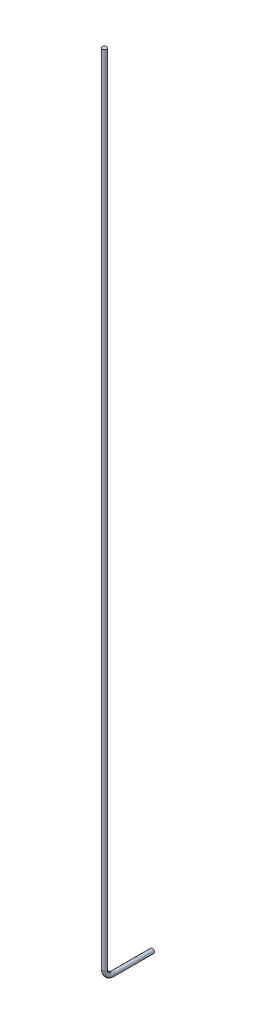
SolidWorks part; units mm, degrees
ref_plane "正面" through (0, 0, 0) normal (0, 0, 1) x (1, 0, 0)
ref_plane "平面" through (0, 0, 0) normal (0, 1, 0) x (1, 0, 0)
ref_plane "右側面" through (0, 0, 0) normal (1, 0, 0) x (0, 0, -1)
sketch "ｽｹｯﾁ1" plane through (0, 0, 0) normal (0, 0, 1) x (1, 0, 0)
  circle A0 centre (0, 0) radius 1.39
  dimension "D1" = 2.78
extrude "ﾎﾞｽ - 押し出し1" add sketch "ｽｹｯﾁ1" along normal blind 20
sketch "ｽｹｯﾁ2" plane through (0, 0, 20) normal (0, 0, 1) x (1, 0, 0)
  circle A1 centre (0, 0) radius 1.39
  circle A2 centre (0, 0) radius 1.39
  dimension "D1" = 0
sketch "ｽｹｯﾁ3" plane through (0, 0, 0) normal (1, 0, 0) x (0, 0, -1)
  line L0 (-20, 0) -> (-25, 0)
  line L1 (-20, 1.39) -> (-20, -1.39) construction
  line L2 (-30, 5) -> (-30, 505)
  line L3 (-20, 1.39) -> (-20, -1.39) construction
  arc A0 (-25, 0) -> (-30, 5) centre (-25, 5) cw
  point P8 (-30, 0)
  dimension "D2" = 5
  dimension "D1" = 10
  dimension "D3" = 500
sweep "ｽｲｰﾌﾟ1" add profiles "ｽｹｯﾁ2" path "ｽｹｯﾁ3"
